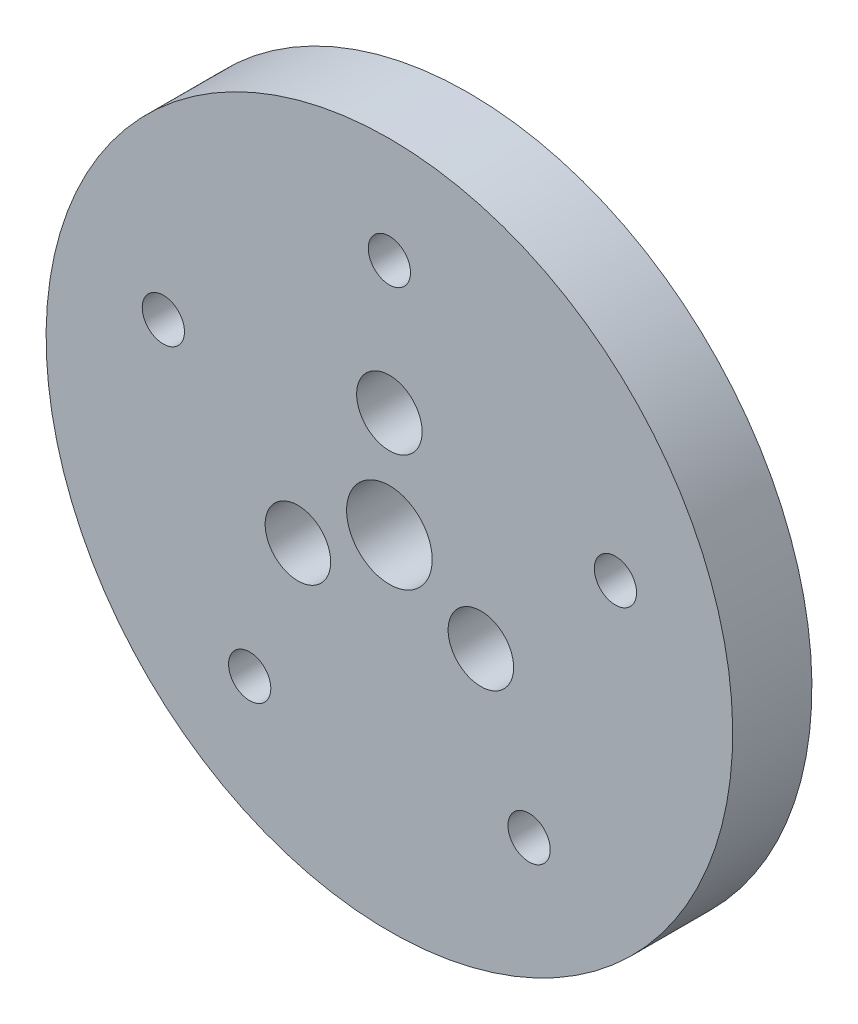
SolidWorks part; units mm, degrees
ref_plane "Ebene vorne" through (0, 0, 0) normal (0, 0, 1) x (1, 0, 0)
ref_plane "Ebene oben" through (0, 0, 0) normal (0, 1, 0) x (1, 0, 0)
ref_plane "Ebene rechts" through (0, 0, 0) normal (1, 0, 0) x (0, 0, -1)
sketch "Skizze1" plane through (0, 0, 0) normal (1, 0, 0) x (0, 0, -1)
  line L1 (0, 0) -> (-44862.1348, 0) construction
  line L2 (0, 0) -> (19.5, 0)
  line L3 (19.5, 0) -> (19.5, 15)
  line L4 (19.5, 15) -> (7.5, 15)
  line L5 (7.5, 15) -> (7.5, 32.5)
  line L6 (7.5, 32.5) -> (0, 32.5)
  line L7 (0, 32.5) -> (0, 0)
  point P0 (0, 0)
  point P10 (0, 0)
  point P12 (0, 0)
  point P13 (0, 0)
  dimension "D1" = 30
  dimension "D2" = 65
  dimension "D3" = 19.5
  dimension "D4" = 12
revolve "Rotation1" add sketch "Skizze1" angle 360 about L1
hole_wizard "Ø4.0 (4) Heat Insert M3" positions "Skizze2" profile "Skizze3" hole size "Ø4.0" standard "ISO" end condition through all
sketch "Skizze2" plane through (0, 0, 0) normal (0, 0, 1) x (1, 0, 0)
  circle A0 centre (0, 0) radius 22.5 construction
  point P7 (0, 22.5)
  dimension "D1" = 45
sketch "Skizze3" plane through (0, 22.5, 0) normal (1, 0, 0) x (0, -1, 0)
  line L0 (0, 0) -> (0, 19.5)
  line L1 (0, 19.5) -> (2, 19.5)
  line L2 (2, 19.5) -> (2, 0)
  line L5 (2, 0) -> (0, 0)
  line L11 (0, -6.35) -> (0, 107.95) construction
  dimension "Bohrerdurchmesser" = 4
  dimension "Bohrungstiefe" = 19.5
hole_wizard "Ø8.1 (8.1) Durchmesser Bohrung1" positions "Skizze4" profile "Skizze5" hole size "Ø8.1" standard "ISO" end condition through all
sketch "Skizze4" plane through (0, 0, 0) normal (0, 0, 1) x (1, 0, 0)
  point P0 (0, 0)
sketch "Skizze5" plane through (0, 0, 0) normal (1, 0, 0) x (0, -1, 0)
  line L0 (0, 0) -> (0, 19.5)
  line L1 (0, 19.5) -> (4.05, 19.5)
  line L2 (4.05, 19.5) -> (4.05, 0)
  line L5 (4.05, 0) -> (0, 0)
  line L11 (0, -6.35) -> (0, 107.95) construction
  dimension "Bohrerdurchmesser" = 8.1
  dimension "Bohrungstiefe" = 19.5
sketch "Skizze8" plane through (0, 0, -19.5) normal (0, 0, -1) x (-1, 0, 0)
  line L0 (0, 0) -> (0, 50000) construction
  circle A0 centre (0, 0) radius 10 construction
  circle A1 centre (0, 10) radius 1.55
  circle A2 centre (8.6603, -5) radius 1.55
  circle A3 centre (-8.6603, -5) radius 1.55
  point P14 (0, 0)
  dimension "D1" = 20
  dimension "D2" = 3.1
  dimension "D3" = 3
extrude "Schnitt-Linear austragen1" cut sketch "Skizze8" against normal blind 12
pattern_circular "Kreismuster1" count 5 over 360 about axis through (0, 0, 0) along (0, 0, 1) of "Ø4.0 (4) Heat Insert M3"
sketch "Skizze9" plane through (0, 0, 0) normal (0, 0, 1) x (1, 0, 0)
  line L0 (0, 0) -> (0, -50000) construction
  circle A0 centre (0, 10) radius 3.1
  circle A1 centre (8.6603, -5) radius 3.1
  circle A2 centre (-8.6603, -5) radius 3.1
  circle A3 centre (0, 0) radius 4.05 construction
  point P12 (0, 0)
  dimension "D1" = 6.2
  dimension "D2" = 10
  dimension "D3" = 3
extrude "Schnitt-Linear austragen2" cut sketch "Skizze9" against normal blind 7.5
